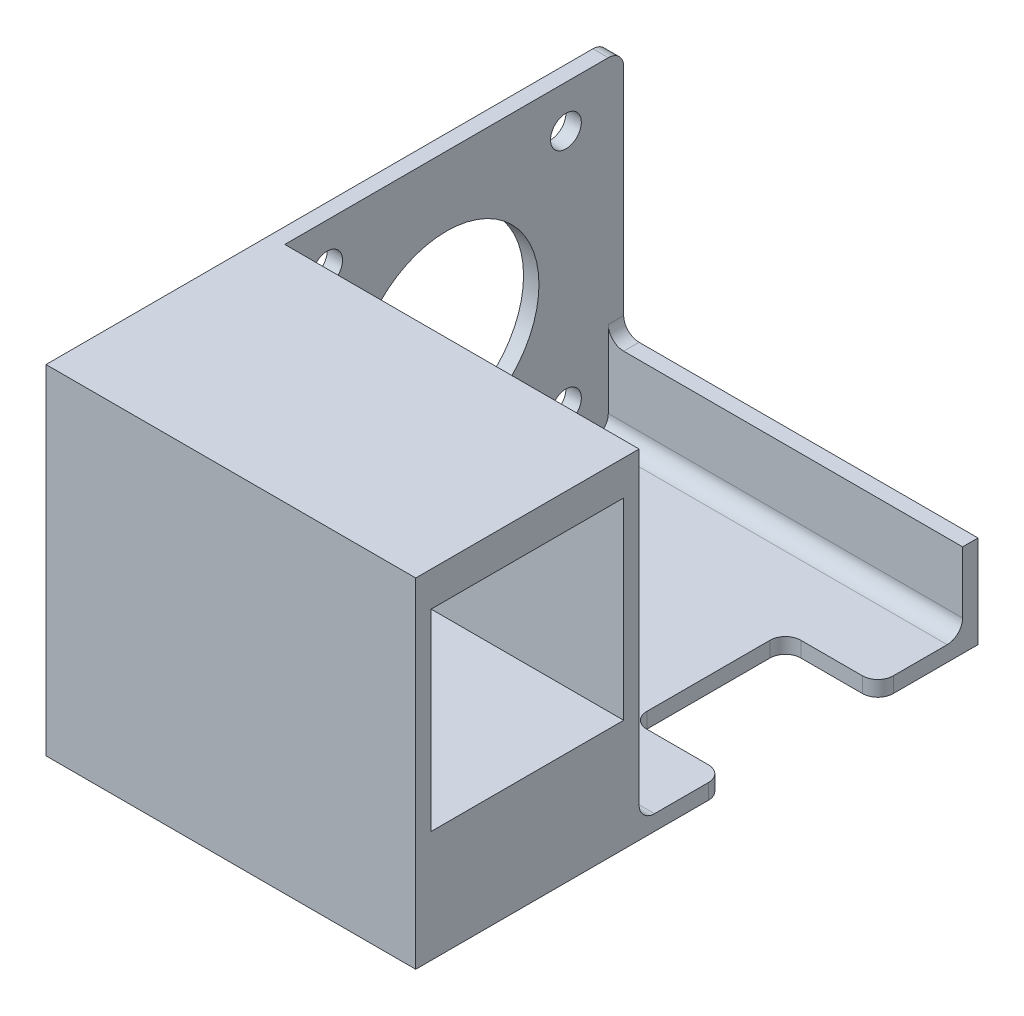
SolidWorks part; units mm, degrees
ref_plane "Front Plane" through (0, 0, 0) normal (0, 0, 1) x (1, 0, 0)
ref_plane "Top Plane" through (0, 0, 0) normal (0, 1, 0) x (1, 0, 0)
ref_plane "Right Plane" through (0, 0, 0) normal (1, 0, 0) x (0, 0, -1)
sketch "Sketch1" plane through (0, 0, 0) normal (0, 0, 1) x (1, 0, 0)
  line L1 (24, 14.5) -> (-24, 14.5)
  line L2 (24, 14.5) -> (24, -14.5)
  line L3 (24, -14.5) -> (-24, -14.5)
  line L4 (-24, 14.5) -> (-24, -14.5)
  line L5 (24, 14.5) -> (-24, -14.5) construction
  line L6 (24, -14.5) -> (-24, 14.5) construction
  point P0 (0, 0)
extrude "Boss-Extrude1" add sketch "Sketch1" along normal blind 29
sketch "Sketch2" plane through (-24, 0, 0) normal (-1, 0, 0) x (0, 0, 1)
  line L0 (29, 14.5) -> (0, -14.5) construction
  line L2 (2, 12.5) -> (27, 12.5)
  line L3 (2, 12.5) -> (2, -12.5)
  line L4 (2, -12.5) -> (27, -12.5)
  line L5 (27, 12.5) -> (27, -12.5)
  line L6 (2, 12.5) -> (27, -12.5) construction
  line L7 (2, -12.5) -> (27, 12.5) construction
  point P4 (14.5, 0)
extrude "Cut-Extrude1" cut sketch "Sketch2" against normal blind 48
sketch "Sketch3" plane through (0, 0, 0) normal (0, 0, -1) x (-1, 0, 0)
  line L0 (24, 14.5) -> (-24, -14.5) construction
  line L2 (24, -23) -> (-24, -23)
  line L3 (24, -23) -> (24, 23)
  line L4 (24, 23) -> (-24, 23)
  line L5 (-24, -23) -> (-24, 23)
  line L6 (24, -23) -> (-24, 23) construction
  line L7 (24, 23) -> (-24, -23) construction
  point P4 (0, 0)
extrude "Boss-Extrude2" add sketch "Sketch3" against normal blind 2
sketch "Sketch4" plane through (0, 0, 0) normal (0, 0, -1) x (-1, 0, 0)
  line L2 (24, -23) -> (-24, -23)
  line L3 (24, -23) -> (24, -21)
  line L4 (24, -21) -> (-24, -21)
  line L5 (-24, -23) -> (-24, -21)
extrude "Boss-Extrude4" add sketch "Sketch4" along normal blind 44 and the other way blind 2
sketch "Sketch5" plane through (0, 0, 0) normal (0, 0, -1) x (-1, 0, 0)
  line L0 (-24, -23) -> (24, -23) construction
  line L1 (24, 23) -> (22, 23)
  line L2 (24, 23) -> (24, -23)
  line L3 (24, -23) -> (22, -23)
  line L4 (22, 23) -> (22, -23)
extrude "Boss-Extrude5" add sketch "Sketch5" along normal blind 44
sketch "Sketch6" plane through (0, 0, -44) normal (0, 0, -1) x (-1, 0, 0)
  line L0 (-24, -21) -> (-24, 23) construction
  line L1 (24, -23) -> (-24, -23)
  line L2 (24, -23) -> (24, -11)
  line L3 (24, -11) -> (-24, -11)
  line L4 (-24, -23) -> (-24, -11)
extrude "Boss-Extrude6" add sketch "Sketch6" against normal blind 2
sketch "Sketch8" plane through (-24, 0, 0) normal (-1, 0, 0) x (0, 0, 1)
  circle A0 centre (-36.5, 15.5) radius 2
  circle A1 centre (-5.5, 15.5) radius 2
  circle A2 centre (-5.5, -15.5) radius 2
  circle A3 centre (-36.5, -15.5) radius 2
  circle A4 centre (-21, 0) radius 12
  point P8 (-21, 0)
  point P13 (-21, 0)
extrude "Cut-Extrude2" cut sketch "Sketch8" against normal blind 2
sketch "Sketch9" plane through (0, -21, 0) normal (0, 1, 0) x (1, 0, 0)
  line L1 (24, 0) -> (24, 42) construction
  line L3 (12, 31) -> (24, 31)
  line L4 (12, 31) -> (12, 11)
  line L5 (12, 11) -> (24, 11)
  line L6 (24, 31) -> (24, 11)
  line L7 (12, 31) -> (24, 11) construction
  line L8 (12, 11) -> (24, 31) construction
  point P5 (18, 21)
extrude "Cut-Extrude3" cut sketch "Sketch9" against normal blind 2
fillet "Fillet4" radius 2 1 edges at (-22, -11, -43)
sketch "Sketch10" plane through (0, 0, 29) normal (0, 0, 1) x (1, 0, 0)
  line L1 (-24, 23) -> (24, 23)
  line L2 (-24, 23) -> (-24, 12.5)
  line L3 (-24, 12.5) -> (24, 12.5)
  line L4 (24, 23) -> (24, 12.5)
  line L5 (24, -23) -> (-24, -23)
  line L6 (24, -23) -> (24, -12.5)
  line L7 (24, -12.5) -> (-24, -12.5)
  line L8 (-24, -23) -> (-24, -12.5)
extrude "Boss-Extrude7" add sketch "Sketch10" against normal blind 29
sketch "Sketch11" plane through (0, 0, 29) normal (0, 0, 1) x (1, 0, 0)
  line L0 (24, -23) -> (24, 23) construction
  line L1 (-24, 23) -> (24, 23)
  line L2 (-24, 23) -> (-24, 21)
  line L3 (-24, 21) -> (24, 21)
  line L4 (24, 23) -> (24, 21)
extrude "Cut-Extrude5" cut sketch "Sketch11" against normal blind 73
sketch "Sketch13" plane through (-24, 0, 0) normal (-1, 0, 0) x (0, 0, 1)
  line L1 (2, 12.5) -> (27, 12.5)
  line L2 (2, 12.5) -> (2, 16.5)
  line L3 (2, 16.5) -> (27, 16.5)
  line L4 (27, 12.5) -> (27, 16.5)
extrude "Cut-Extrude6" cut sketch "Sketch13" against normal blind 73
sketch "Sketch14" plane through (-24, 0, 0) normal (-1, 0, 0) x (0, 0, 1)
  line L1 (29, -23) -> (1, -23)
  line L2 (29, -23) -> (29, -8.5)
  line L3 (29, -8.5) -> (1, -8.5)
  line L4 (1, -23) -> (1, -8.5)
extrude "Boss-Extrude10" add sketch "Sketch14" against normal blind 48
fillet "Fillet5" radius 2 1 edges at (1, -21, 0)
fillet "Fillet6" radius 2 1 edges at (1, -21, -42)
fillet "Fillet7" radius 2 1 edges at (-23, 21, -44)
fillet "Fillet8" radius 2 4 edges at (12, -22, -31) (24, -22, -31) (12, -22, -11) (24, -22, -11)
